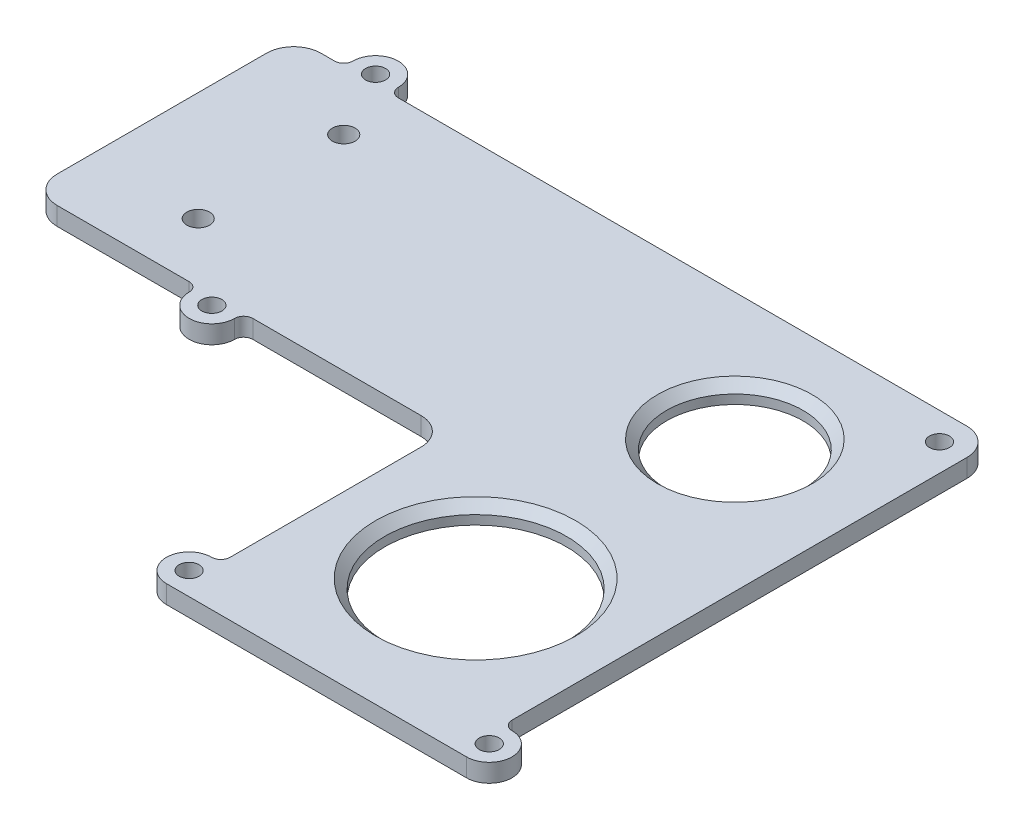
SolidWorks part; units mm, degrees
ref_plane "Alzado" through (0, 0, 0) normal (0, 0, 1) x (1, 0, 0)
ref_plane "Planta" through (0, 0, 0) normal (0, 1, 0) x (1, 0, 0)
ref_plane "Vista lateral" through (0, 0, 0) normal (1, 0, 0) x (0, 0, -1)
sketch "Croquis1" plane through (0, 0, 0) normal (0, 1, 0) x (1, 0, 0)
  line L0 (-43, 30) -> (-28.5, 30)
  line L1 (0, 27) -> (0, 6)
  line L2 (0, 0) -> (31, 0)
  line L3 (31, 6) -> (31, 56)
  line L4 (28, 59) -> (-34.5, 59)
  line L5 (-46, 56) -> (-46, 33)
  line L7 (-1, 0) -> (0, 0)
  line L8 (15.5, 0) -> (15.5, 2) construction
  line L10 (32, 0) -> (31, 0)
  line L13 (-21.5, 30) -> (-3, 30)
  line L14 (-41.5, 59) -> (-43, 59)
  arc A0 (31, 56) -> (28, 59) centre (28, 56) ccw
  arc A1 (-3, 30) -> (0, 27) centre (-3, 27) cw
  arc A2 (-43, 30) -> (-46, 33) centre (-43, 33) cw
  arc A3 (-43, 59) -> (-46, 56) centre (-43, 56) ccw
  circle A4 centre (15.5, 17.5) radius 10
  circle A5 centre (16.5, 45) radius 7.5
  circle A6 centre (32, 2.5) radius 1.1
  arc A7 (32, 0) -> (32, 5) centre (32, 2.5) ccw
  arc A8 (-35.5, 60) -> (-40.5, 60) centre (-38, 60) ccw
  circle A9 centre (-38, 60) radius 1.1
  arc A10 (32, 5) -> (31, 6) centre (32, 6) cw
  arc A11 (-1, 5) -> (0, 6) centre (-1, 6) ccw
  arc A12 (-1, 0) -> (-1, 5) centre (-1, 2.5) cw
  circle A13 centre (-1, 2.5) radius 1.1
  arc A14 (-40.5, 60) -> (-41.5, 59) centre (-41.5, 60) cw
  arc A15 (-35.5, 60) -> (-34.5, 59) centre (-34.5, 60) ccw
  arc A16 (-27.5, 29) -> (-28.5, 30) centre (-28.5, 29) ccw
  arc A17 (-22.5, 29) -> (-21.5, 30) centre (-21.5, 29) cw
  circle A18 centre (-25, 29) radius 1.1
  arc A19 (-22.5, 29) -> (-27.5, 29) centre (-25, 29) cw
  circle A20 centre (28, 56) radius 1.1
  dimension "D1" = 3
  dimension "D2" = 20
  dimension "D3" = 15
  dimension "D4" = 2.2
  dimension "D5" = 5
  dimension "D6" = 2.5
  dimension "D7" = 2.2
  dimension "D8" = 2.5
  dimension "D9" = 2.2
extrude "Saliente-Extruir1" add sketch "Croquis1" along normal blind 2
chamfer "Chaflán1" distance 1 angle 45 2 edges at (16.5, 2, -37.5) (15.5, 2, -7.5)
sketch "Croquis2" plane through (0, 2, 0) normal (0, 1, 0) x (1, 0, 0)
  line L0 (-34, 52.5) -> (-34, 36.5) construction
  line L1 (-46, 56) -> (-46, 33) construction
  circle A0 centre (-34, 52.5) radius 1.25
  circle A1 centre (-34, 36.5) radius 1.25
  point P4 (-46, 44.5)
  point P7 (-34, 44.5)
  dimension "D1" = 16
  dimension "D2" = 2.5
  dimension "D3" = 12
extrude "Cortar-Extruir1" cut sketch "Croquis2" against normal through all
